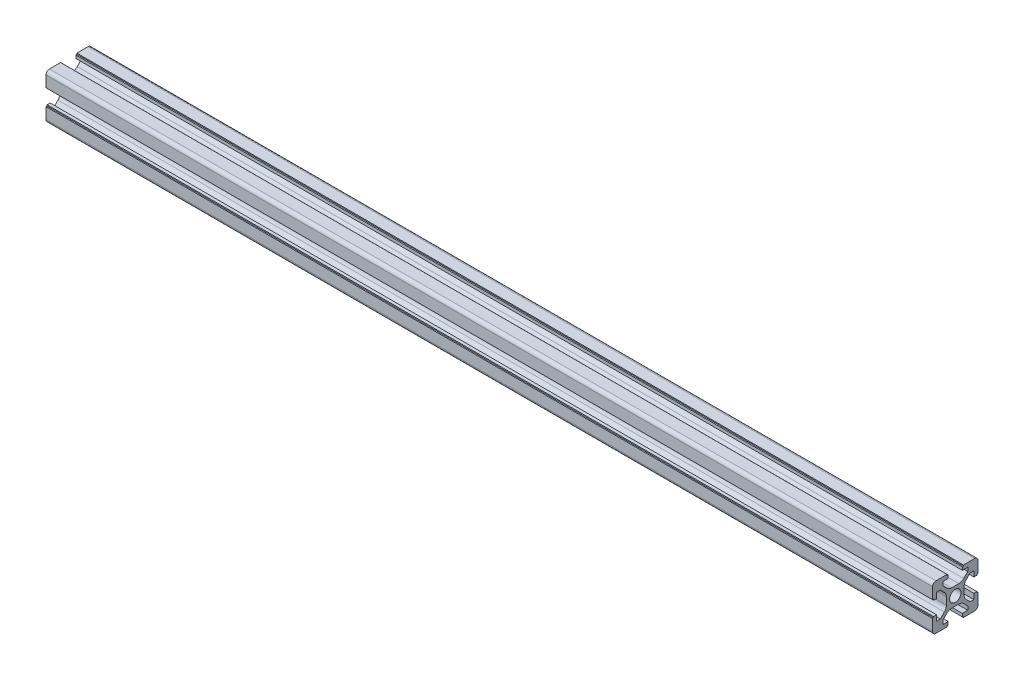
SolidWorks part; units mm, degrees
ref_plane "前视基准面" through (0, 0, 0) normal (0, 0, 1) x (1, 0, 0)
ref_plane "上视基准面" through (0, 0, 0) normal (0, 1, 0) x (1, 0, 0)
ref_plane "右视基准面" through (0, 0, 0) normal (1, 0, 0) x (0, 0, -1)
sketch "草图1" plane through (0, 0, 0) normal (1, 0, 0) x (0, 0, -1)
  line L0 (0, 0) -> (-10, 0) construction
  line L1 (0, 0) -> (0, 10) construction
  line L2 (0, 0) -> (-10, 10) construction
  line L3 (-10, 10) -> (-10, 3.6)
  line L4 (-10, 3.6) -> (-9.531, 3.6)
  line L5 (-9.531, 3.6) -> (-9.531, 3.1)
  line L6 (-9.531, 3.1) -> (-8.2, 3.1)
  line L7 (-8.2, 3.1) -> (-8.2, 5.5)
  line L8 (-8.2, 5.5) -> (-6.5607, 5.5)
  line L9 (-6.5607, 5.5) -> (-3.9, 2.8393)
  line L10 (-3.9, 2.8393) -> (-3.9, 0)
  line L11 (-3.6, 9.531) -> (-3.1, 9.531)
  line L12 (-2.8393, 3.9) -> (0, 3.9)
  line L13 (-5.5, 6.5607) -> (-2.8393, 3.9)
  line L14 (-5.5, 8.2) -> (-5.5, 6.5607)
  line L15 (-3.1, 8.2) -> (-5.5, 8.2)
  line L16 (-3.1, 9.531) -> (-3.1, 8.2)
  line L17 (-3.6, 10) -> (-3.6, 9.531)
  line L18 (-10, 10) -> (-3.6, 10)
  line L19 (0, 0) -> (0, 10) construction
  line L20 (0, 0) -> (10, 0) construction
  line L21 (0, 0) -> (10, 10) construction
  line L22 (10, 10) -> (3.6, 10)
  line L23 (3.6, 10) -> (3.6, 9.531)
  line L24 (3.6, 9.531) -> (3.1, 9.531)
  line L25 (3.1, 9.531) -> (3.1, 8.2)
  line L26 (3.1, 8.2) -> (5.5, 8.2)
  line L27 (5.5, 8.2) -> (5.5, 6.5607)
  line L28 (5.5, 6.5607) -> (2.8393, 3.9)
  line L29 (2.8393, 3.9) -> (0, 3.9)
  line L30 (9.531, 3.6) -> (9.531, 3.1)
  line L31 (3.9, 2.8393) -> (3.9, 0)
  line L32 (6.5607, 5.5) -> (3.9, 2.8393)
  line L33 (8.2, 5.5) -> (6.5607, 5.5)
  line L34 (8.2, 3.1) -> (8.2, 5.5)
  line L35 (9.531, 3.1) -> (8.2, 3.1)
  line L36 (10, 3.6) -> (9.531, 3.6)
  line L37 (10, 10) -> (10, 3.6)
  line L38 (0, 0) -> (10, 0) construction
  line L39 (0, 0) -> (0, -10) construction
  line L40 (0, 0) -> (10, -10) construction
  line L41 (10, -10) -> (10, -3.6)
  line L42 (10, -3.6) -> (9.531, -3.6)
  line L43 (9.531, -3.6) -> (9.531, -3.1)
  line L44 (9.531, -3.1) -> (8.2, -3.1)
  line L45 (8.2, -3.1) -> (8.2, -5.5)
  line L46 (8.2, -5.5) -> (6.5607, -5.5)
  line L47 (6.5607, -5.5) -> (3.9, -2.8393)
  line L48 (3.9, -2.8393) -> (3.9, 0)
  line L49 (3.6, -9.531) -> (3.1, -9.531)
  line L50 (2.8393, -3.9) -> (0, -3.9)
  line L51 (5.5, -6.5607) -> (2.8393, -3.9)
  line L52 (5.5, -8.2) -> (5.5, -6.5607)
  line L53 (3.1, -8.2) -> (5.5, -8.2)
  line L54 (3.1, -9.531) -> (3.1, -8.2)
  line L55 (3.6, -10) -> (3.6, -9.531)
  line L56 (10, -10) -> (3.6, -10)
  line L57 (0, 0) -> (0, -10) construction
  line L58 (0, 0) -> (-10, 0) construction
  line L59 (0, 0) -> (-10, -10) construction
  line L60 (-10, -10) -> (-3.6, -10)
  line L61 (-3.6, -10) -> (-3.6, -9.531)
  line L62 (-3.6, -9.531) -> (-3.1, -9.531)
  line L63 (-3.1, -9.531) -> (-3.1, -8.2)
  line L64 (-3.1, -8.2) -> (-5.5, -8.2)
  line L65 (-5.5, -8.2) -> (-5.5, -6.5607)
  line L66 (-5.5, -6.5607) -> (-2.8393, -3.9)
  line L67 (-2.8393, -3.9) -> (0, -3.9)
  line L68 (-9.531, -3.6) -> (-9.531, -3.1)
  line L69 (-3.9, -2.8393) -> (-3.9, 0)
  line L70 (-6.5607, -5.5) -> (-3.9, -2.8393)
  line L71 (-8.2, -5.5) -> (-6.5607, -5.5)
  line L72 (-8.2, -3.1) -> (-8.2, -5.5)
  line L73 (-9.531, -3.1) -> (-8.2, -3.1)
  line L74 (-10, -3.6) -> (-9.531, -3.6)
  line L75 (-10, -10) -> (-10, -3.6)
  arc A0 (0, 2.5) -> (-2.5, 0) centre (0, 0) ccw
  arc A1 (2.5, 0) -> (0, 2.5) centre (0, 0) ccw
  arc A2 (0, -2.5) -> (2.5, 0) centre (0, 0) ccw
  arc A3 (-2.5, 0) -> (0, -2.5) centre (0, 0) ccw
  point P89 (0, 0)
  dimension "D3" = 5
  dimension "D1" = 10
  dimension "D2" = 10
  dimension "D4" = 10
  dimension "D5" = 1.8
  dimension "D6" = 5.5
  dimension "D7" = 3.1
  dimension "D8" = 3.6
  dimension "D9" = 6.1
  dimension "D10" = 0.75
  dimension "D11" = 4
extrude "凸台-拉伸1" add sketch "草图1" along normal blind 390
fillet "圆角1" radius 1.5 4 edges at (195, -10, -10) (195, -10, 10) (195, 10, -10) (195, 10, 10)
fillet "圆角2" radius 3 8 edges at (195, -3.9, 2.8393) (195, -3.9, -2.8393) (195, -2.8393, -3.9) (195, 2.8393, -3.9) (195, 2.8393, 3.9) (195, -2.8393, 3.9) (195, 3.9, 2.8393) (195, 3.9, -2.8393)
